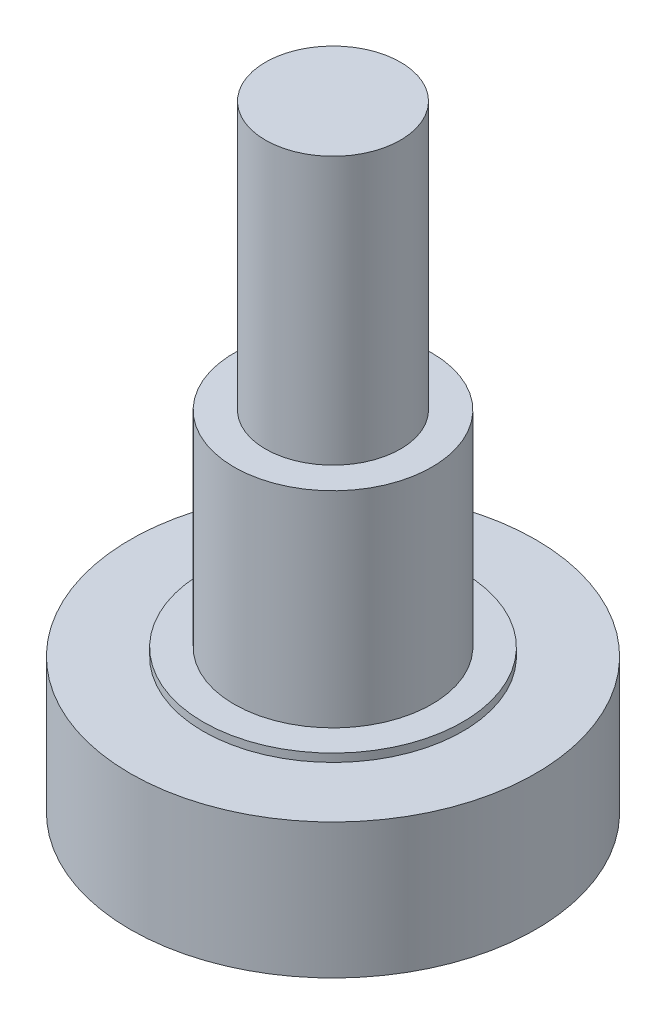
SolidWorks part; units mm, degrees
ref_plane "Front" through (0, 0, 0) normal (0, 0, 1) x (1, 0, 0)
ref_plane "Top" through (0, 0, 0) normal (0, 1, 0) x (1, 0, 0)
ref_plane "Right" through (0, 0, 0) normal (1, 0, 0) x (0, 0, -1)
sketch "Sketch1" plane through (0, 0, 0) normal (0, 0, 1) x (1, 0, 0)
  line L0 (0, 0) -> (-9.525, 0)
  line L1 (-9.525, 0) -> (-9.525, 6.35)
  line L2 (-9.525, 6.35) -> (-6.096, 6.35)
  line L3 (-6.096, 6.35) -> (-6.096, 6.731)
  line L4 (-6.096, 6.731) -> (-4.6482, 6.731)
  line L5 (-4.6482, 6.731) -> (-4.6482, 16.383)
  line L6 (-4.6482, 16.383) -> (-3.175, 16.383)
  line L7 (-3.175, 16.383) -> (-3.175, 28.956)
  line L8 (-3.175, 28.956) -> (0, 28.956)
  line L9 (0, 28.956) -> (0, 0)
  line L10 (0, 0) -> (0, -22.8649) construction
  dimension "D1" = 19.05
  dimension "D2" = 12.192
  dimension "D3" = 9.2964
  dimension "D4" = 6.35
  dimension "D5" = 6.35
  dimension "D6" = 0.381
  dimension "D7" = 9.652
  dimension "D8" = 22.225
revolve "Revolve1" add sketch "Sketch1" angle 360 about L10
